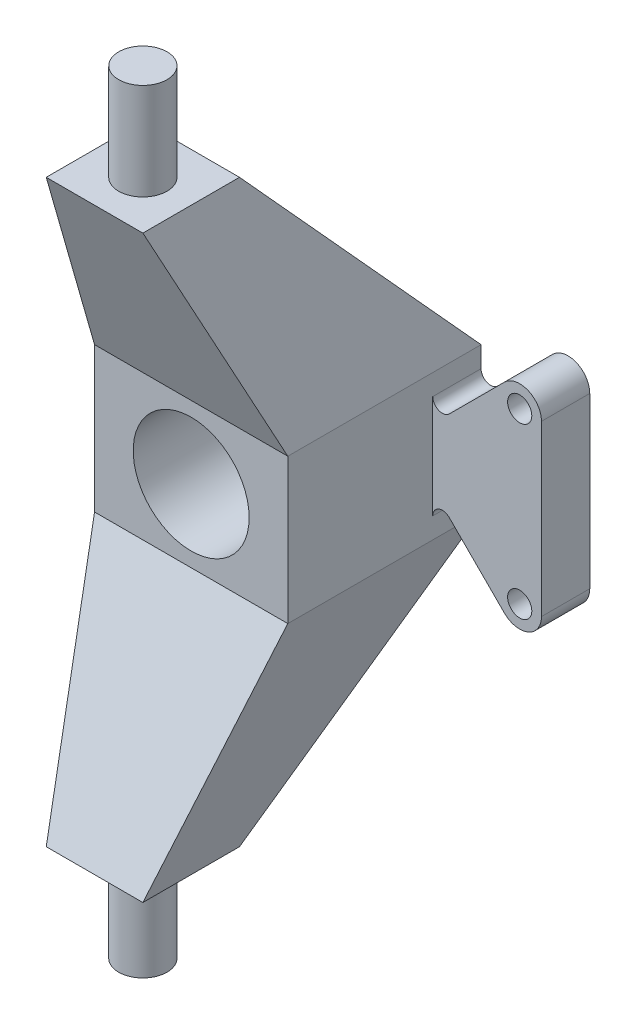
SolidWorks part; units mm, degrees
material "Acier allié inoxydable"
ref_plane "Plan de face" through (0, 0, 0) normal (0, 0, 1) x (1, 0, 0)
ref_plane "Plan de dessus" through (0, 0, 0) normal (0, 1, 0) x (1, 0, 0)
ref_plane "Plan de droite" through (0, 0, 0) normal (1, 0, 0) x (0, 0, -1)
sketch "Esquisse1" plane through (0, 0, 0) normal (0, 0, 1) x (1, 0, 0)
  line L1 (-20, 15) -> (20, 15)
  line L2 (-20, 15) -> (-20, -15)
  line L3 (-20, -15) -> (20, -15)
  line L4 (20, 15) -> (20, -15)
  circle A0 centre (0, 0) radius 12
  point P7 (0, 15)
  point P8 (-20, 0)
  dimension "D1" = 24
  dimension "D2" = 40
  dimension "D3" = 30
extrude "Boss.-Extru.1" add sketch "Esquisse1" against normal blind 40
ref_plane "Plan1" through (0, 60, 0) normal (0, 1, 0) x (1, 0, 0)
sketch "Esquisse2" plane through (0, 60, 0) normal (0, 1, 0) x (1, 0, 0)
  line L0 (20, 40) -> (-20, 40) construction
  line L1 (10, 0) -> (-10, 0)
  line L2 (10, 0) -> (10, -20)
  line L3 (10, -20) -> (-10, -20)
  line L4 (-10, 0) -> (-10, -20)
  point P6 (0, 0)
  dimension "D1" = 20
  dimension "D2" = 20
  dimension "D3" = 40
loft "Lissage1" add profiles "Esquisse2" section "Esquisse2" section face at (0, 15, -20)
sketch "Esquisse3" plane through (0, 60, 0) normal (0, 1, 0) x (1, 0, 0)
  circle A0 centre (0, -10) radius 5
  dimension "D1" = 10
extrude "Boss.-Extru.2" add sketch "Esquisse3" along normal blind 20
mirror "Symétrie7" about plane through (0, 0, 0) normal (0, 1, 0) of bodies 103
sketch "Esquisse4" plane through (0, 0, -40) normal (0, 0, -1) x (-1, 0, 0)
  line L0 (-20, 5.864) -> (-34.818, 20.682)
  line L1 (-20, -15) -> (-20, 15) construction
  line L2 (-42.5, 17.5) -> (-42.5, -17.5)
  line L3 (-34.818, -20.682) -> (-20, -5.864)
  line L7 (-20, 5.864) -> (-20, -5.864)
  circle A0 centre (-38, 17.5) radius 2.5
  circle A1 centre (-38, -17.5) radius 2.5
  arc A2 (-34.818, 20.682) -> (-42.5, 17.5) centre (-38, 17.5) ccw
  arc A3 (-42.5, -17.5) -> (-34.818, -20.682) centre (-38, -17.5) ccw
  point P4 (-42.5, 0)
  dimension "D6" = 4.5
  dimension "D7" = 4.5
  dimension "D8" = 4.5
  dimension "D9" = 5
  dimension "D10" = 5
  dimension "D5" = 0
  dimension "D1" = 45
  dimension "D2" = 45
  dimension "D3" = 35
  dimension "D4" = 17.5
extrude "Boss.-Extru.3" add sketch "Esquisse4" against normal blind 10
fillet "Congé1" radius 2 1 edges at (20, 5.864, -35)
fillet "Congé2" radius 2 1 edges at (20, -5.864, -35)
equation "\"A\"= 40"
equation "\"B\"= 120"
equation "\"C\"= 20"
equation "\"D\"= \"B\" / 4"
equation "\"E\"= \"C\" / 2"
equation "\"D2@Esquisse1\"=\"C\"+20"
equation "\"D3@Esquisse1\"=\"D\""
equation "\"D1@Boss.-Extru.1\"=\"A\""
equation "\"D1@Esquisse2\"=\"C\""
equation "\"D2@Esquisse2\"=\"C\""
equation "\"D1@Esquisse3\"=\"E\""
equation "\"D1@Boss.-Extru.2\"=\"C\""
